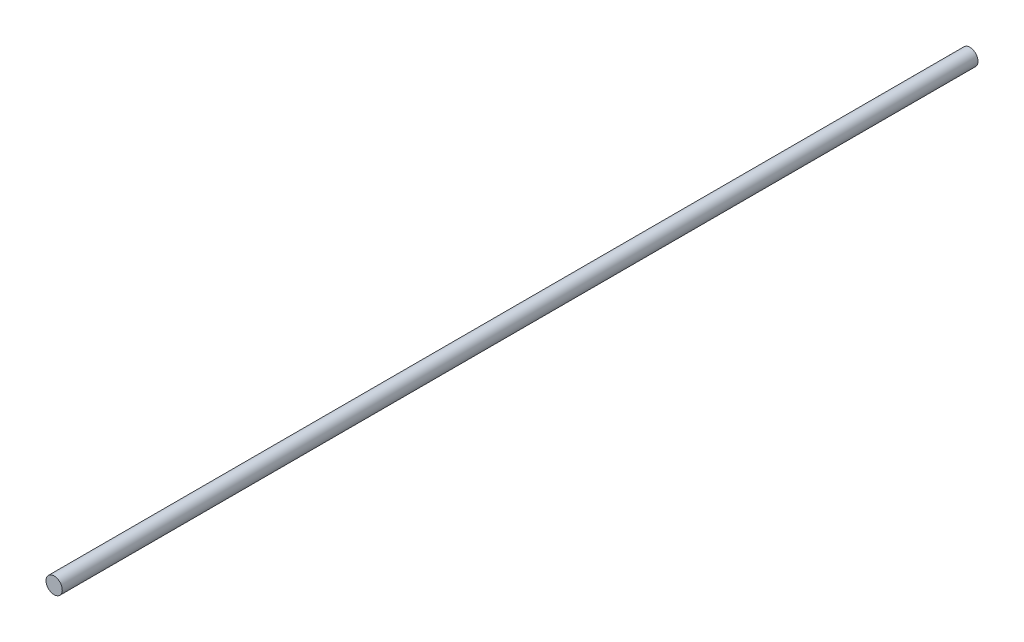
SolidWorks part; units mm, degrees
ref_plane "Front Plane" through (0, 0, 0) normal (0, 0, 1) x (1, 0, 0)
ref_plane "Top Plane" through (0, 0, 0) normal (0, 1, 0) x (1, 0, 0)
ref_plane "Right Plane" through (0, 0, 0) normal (1, 0, 0) x (0, 0, -1)
sketch "Sketch1" plane through (0, 0, 0) normal (0, 0, 1) x (1, 0, 0)
  circle A0 centre (0, 0) radius 4
  dimension "D1" = 8
extrude "Boss-Extrude1" add sketch "Sketch1" along normal blind 450
